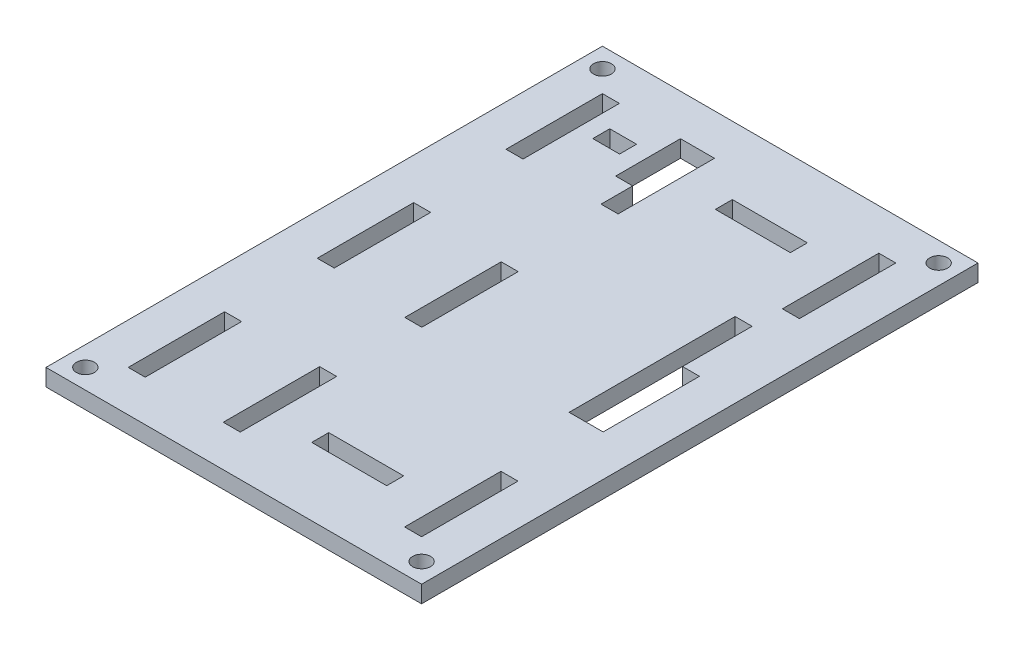
SolidWorks part; units mm, degrees
ref_plane "Front Plane" through (0, 0, 0) normal (0, 0, 1) x (1, 0, 0)
ref_plane "Top Plane" through (0, 0, 0) normal (0, 1, 0) x (1, 0, 0)
ref_plane "Right Plane" through (0, 0, 0) normal (1, 0, 0) x (0, 0, -1)
sketch "Sketch2" plane through (0, 0, 0) normal (0, 1, 0) x (1, 0, 0)
  line L1 (-27.3923, -44.2755) -> (27.3923, -44.2755)
  line L2 (-27.3923, -44.2755) -> (-27.3923, 44.2755)
  line L3 (-27.3923, 44.2755) -> (27.3923, 44.2755)
  line L4 (27.3923, -44.2755) -> (27.3923, 44.2755)
  line L5 (-27.3923, -44.2755) -> (27.3923, 44.2755) construction
  line L6 (-27.3923, 44.2755) -> (27.3923, -44.2755) construction
  point P0 (0, 0)
  dimension "D1" = 54.7846
  dimension "D2" = 88.551
extrude "Boss-Extrude1" add sketch "Sketch2" along normal blind 3.175
sketch "Sketch7" plane through (0, 3.175, 0) normal (0, 1, 0) x (1, 0, 0)
  line L0 (-27.3923, 44.2755) -> (-27.3923, -44.2755) construction
  line L1 (-27.3923, 44.2755) -> (-24.2173, 44.2755)
  line L2 (-27.3923, 44.2755) -> (-27.3923, 26.2755)
  line L3 (-27.3923, 26.2755) -> (-24.2173, 26.2755)
  line L4 (-24.2173, 44.2755) -> (-24.2173, 26.2755)
  line L5 (-27.3923, 9.0255) -> (-24.2173, 9.0255)
  line L6 (-27.3923, 9.0255) -> (-27.3923, -8.9745)
  line L7 (-27.3923, -8.9745) -> (-24.2173, -8.9745)
  line L8 (-24.2173, 9.0255) -> (-24.2173, -8.9745)
  line L9 (-27.3923, -44.2755) -> (27.3923, -44.2755) construction
  line L10 (-27.3923, -26.2755) -> (-24.2173, -26.2755)
  line L11 (-27.3923, -26.2755) -> (-27.3923, -44.2755)
  line L12 (-27.3923, -44.2755) -> (-24.2173, -44.2755)
  line L13 (-24.2173, -26.2755) -> (-24.2173, -44.2755)
  line L14 (27.3923, -44.2755) -> (27.3923, 44.2755) construction
  line L15 (27.3923, -44.2755) -> (24.2173, -44.2755)
  line L16 (27.3923, -44.2755) -> (27.3923, -26.2755)
  line L17 (27.3923, -26.2755) -> (24.2173, -26.2755)
  line L18 (24.2173, -44.2755) -> (24.2173, -26.2755)
  line L19 (27.3923, -10.3745) -> (24.2173, -10.3745)
  line L20 (27.3923, -10.3745) -> (27.3923, 7.6255)
  line L21 (27.3923, 7.6255) -> (24.2173, 7.6255)
  line L22 (24.2173, -10.3745) -> (24.2173, 7.6255)
  line L23 (27.3923, 44.2755) -> (-27.3923, 44.2755) construction
  line L24 (24.2173, -10.3745) -> (21.0423, -10.3745)
  line L25 (24.2173, -10.3745) -> (24.2173, 20.6255)
  line L26 (24.2173, 20.6255) -> (21.0423, 20.6255)
  line L27 (21.0423, -10.3745) -> (21.0423, 20.6255)
  line L28 (27.3923, 44.2755) -> (24.2173, 44.2755)
  line L29 (27.3923, 44.2755) -> (27.3923, 26.2755)
  line L30 (27.3923, 26.2755) -> (24.2173, 26.2755)
  line L31 (24.2173, 44.2755) -> (24.2173, 26.2755)
  line L32 (-12.8173, 44.2755) -> (-9.6423, 44.2755)
  line L33 (-12.8173, 44.2755) -> (-12.8173, 32.1755)
  line L34 (-12.8173, 32.1755) -> (-9.6423, 32.1755)
  line L35 (-9.6423, 44.2755) -> (-9.6423, 32.1755)
  line L37 (-9.6423, 44.2755) -> (-6.4673, 44.2755)
  line L38 (-9.6423, 44.2755) -> (-9.6423, 26.2755)
  line L39 (-9.6423, 26.2755) -> (-6.4673, 26.2755)
  line L40 (-6.4673, 44.2755) -> (-6.4673, 26.2755)
  line L41 (-21.0173, 39.2755) -> (-16.0173, 39.2755)
  line L42 (-21.0173, 39.2755) -> (-21.0173, 36.1005)
  line L43 (-21.0173, 36.1005) -> (-16.0173, 36.1005)
  line L44 (-16.0173, 39.2755) -> (-16.0173, 36.1005)
  line L45 (1.875, 39.2755) -> (15.875, 39.2755)
  line L46 (1.875, 39.2755) -> (1.875, 36.1005)
  line L47 (1.875, 36.1005) -> (15.875, 36.1005)
  line L48 (15.875, 39.2755) -> (15.875, 36.1005)
  line L49 (-9.6423, 7.6255) -> (-6.4673, 7.6255)
  line L50 (-9.6423, 7.6255) -> (-9.6423, -10.3745)
  line L51 (-9.6423, -10.3745) -> (-6.4673, -10.3745)
  line L52 (-6.4673, 7.6255) -> (-6.4673, -10.3745)
  line L53 (-9.6423, -26.2755) -> (-6.4673, -26.2755)
  line L54 (-9.6423, -26.2755) -> (-9.6423, -44.2755)
  line L55 (-9.6423, -44.2755) -> (-6.4673, -44.2755)
  line L56 (-6.4673, -26.2755) -> (-6.4673, -44.2755)
  line L57 (1.875, -36.1005) -> (15.875, -36.1005)
  line L58 (1.875, -36.1005) -> (1.875, -39.2755)
  line L59 (1.875, -39.2755) -> (15.875, -39.2755)
  line L60 (15.875, -36.1005) -> (15.875, -39.2755)
  line M29 (27.3923, -44.2755) -> (27.3923, 44.2755)
  line M30 (27.3923, 44.2755) -> (-27.3923, 44.2755)
  line M31 (-27.3923, 44.2755) -> (-27.3923, -44.2755)
  line M32 (-27.3923, -44.2755) -> (27.3923, -44.2755)
  dimension "D1" = 3.175
  dimension "D2" = 3.175
  dimension "D3" = 3.175
  dimension "D4" = 3.175
  dimension "D5" = 3.175
  dimension "D6" = 3.175
  dimension "D7" = 3.175
  dimension "D8" = 3.175
  dimension "D9" = 3.175
  dimension "D10" = 3.175
  dimension "D11" = 3.175
  dimension "D12" = 3.175
  dimension "D13" = 3.175
  dimension "D14" = 3.175
  dimension "D15" = 0
  dimension "D16" = 0
  dimension "D17" = 18
  dimension "D18" = 18
  dimension "D19" = 18
  dimension "D20" = 18
  dimension "D21" = 18
  dimension "D22" = 18
  dimension "D23" = 17.25
  dimension "D24" = 3.2
  dimension "D25" = 12.1
  dimension "D26" = 5
  dimension "D27" = 5
  dimension "D28" = 11.4
  dimension "D29" = 18
  dimension "D30" = 18
  dimension "D31" = 18
  dimension "D32" = 18.65
  dimension "D33" = 18.65
  dimension "D34" = 31
  dimension "D35" = 14
  dimension "D36" = 8.3423
  dimension "D37" = 5
  dimension "D38" = 0
  dimension "D39" = 5
  dimension "D40" = 14
extrude "Cut-Extrude1" cut sketch "Sketch7" against normal blind 10 contours L4 L3 M30 M31 | L44 L41 L42 L43 | L35 L33 L34 M30 | L40 L35 L38 L39 M30 | L48 L45 L46 L47 | L31 L30 M30 M29 | L27 L24 L22 L25 L26 | L22 L19 L21 M29 | L52 L49 L50 L51 | L8 L5 L7 M31 | L13 L10 M31 M32 | L56 L53 L54 M32 | L60 L57 L58 L59 | L18 L17 L16 L15
sketch "Sketch8" plane through (0, 3.175, 0) normal (0, 1, 0) x (1, 0, 0)
  line L0 (-31.3923, 48.2755) -> (31.3923, 48.2755)
  line L3 (31.3923, -48.2755) -> (31.3923, 48.2755)
  line L10 (-31.3923, -48.2755) -> (31.3923, -48.2755)
  line L13 (-27.3923, -44.2755) -> (27.3923, -44.2755)
  line L14 (-27.3923, -44.2755) -> (-27.3923, 44.2755)
  line L19 (-27.3923, 44.2755) -> (27.3923, 44.2755)
  line L20 (27.3923, -44.2755) -> (27.3923, 44.2755)
  line L21 (-27.3923, -44.2755) -> (27.3923, 44.2755) construction
  line L22 (-27.3923, 44.2755) -> (27.3923, -44.2755) construction
  line L23 (-31.3923, -48.2755) -> (-31.3923, 48.2755)
  point P4 (0, 0)
  dimension "D1" = 4
extrude "Boss-Extrude2" add sketch "Sketch8" against normal up to surface (3.175 mm away)
sketch "Sketch12" plane through (0, 3.175, 0) normal (0, 1, 0) x (1, 0, 0)
  circle A0 centre (-31.3923, 48.2755) radius 1.675
  circle A1 centre (31.3923, 48.2755) radius 1.675
  circle A2 centre (31.3923, -48.2755) radius 1.675
  circle A3 centre (-31.3923, -48.2755) radius 1.675
  circle A4 centre (-31.3923, -48.2755) radius 3.675
  circle A5 centre (31.3923, -48.2755) radius 3.675
  circle A6 centre (31.3923, 48.2755) radius 3.675
  circle A7 centre (-31.3923, 48.2755) radius 3.675
  dimension "D1" = 3.35
  dimension "D2" = 3.35
  dimension "D3" = 3.35
  dimension "D4" = 3.35
  dimension "D5" = 2
extrude "Boss-Extrude4" add sketch "Sketch12" against normal up to surface (3.175 mm away) up to face at (25.8048, 0, -35.2755)
sketch "Sketch13" plane through (0, 3.175, 0) normal (0, 1, 0) x (1, 0, 0)
  circle A0 centre (-31.3923, 48.2755) radius 1.675
  circle A1 centre (31.3923, 48.2755) radius 1.675
  circle A2 centre (31.3923, -48.2755) radius 1.675
  circle A3 centre (-31.3923, -48.2755) radius 1.675
  dimension "D1" = 96.551
  dimension "D2" = 62.7846
extrude "Cut-Extrude4" cut sketch "Sketch13" against normal blind 10
sketch "Sketch14" plane through (0, 3.175, 0) normal (0, 1, 0) x (1, 0, 0)
  line L1 (-35.0673, -51.9505) -> (35.0673, -51.9505)
  line L2 (-35.0673, -51.9505) -> (-35.0673, 51.9505)
  line L3 (-35.0673, 51.9505) -> (35.0673, 51.9505)
  line L4 (35.0673, -51.9505) -> (35.0673, 51.9505)
  line L5 (-35.0673, -51.9505) -> (35.0673, 51.9505) construction
  line L6 (-35.0673, 51.9505) -> (35.0673, -51.9505) construction
  line L7 (-31.3923, -48.2755) -> (31.3923, -48.2755)
  line L8 (-31.3923, -48.2755) -> (-31.3923, 48.2755)
  line L9 (-31.3923, 48.2755) -> (31.3923, 48.2755)
  line L10 (31.3923, -48.2755) -> (31.3923, 48.2755)
  line L11 (-31.3923, -48.2755) -> (31.3923, 48.2755) construction
  line L12 (-31.3923, 48.2755) -> (31.3923, -48.2755) construction
  circle A0 centre (-31.3923, 48.2755) radius 3.675
  circle A1 centre (31.3923, 48.2755) radius 3.675
  circle A2 centre (31.3923, -48.2755) radius 3.675
  circle A3 centre (-31.3923, -48.2755) radius 3.675
  point P0 (0, 0)
  point P6 (0, 0)
extrude "Boss-Extrude5" add sketch "Sketch14" against normal up to surface (3.175 mm away) contours A3 L8 A0 L2 | A1 L3 A0 L9 | A0 L3 L2 | A2 L4 A1 L10 | A1 L4 L3 | A2 L1 L4 | A3 L1 A2 L7 | A3 L2 L1 up to face at (-31.3923, 0, 46.6005)
